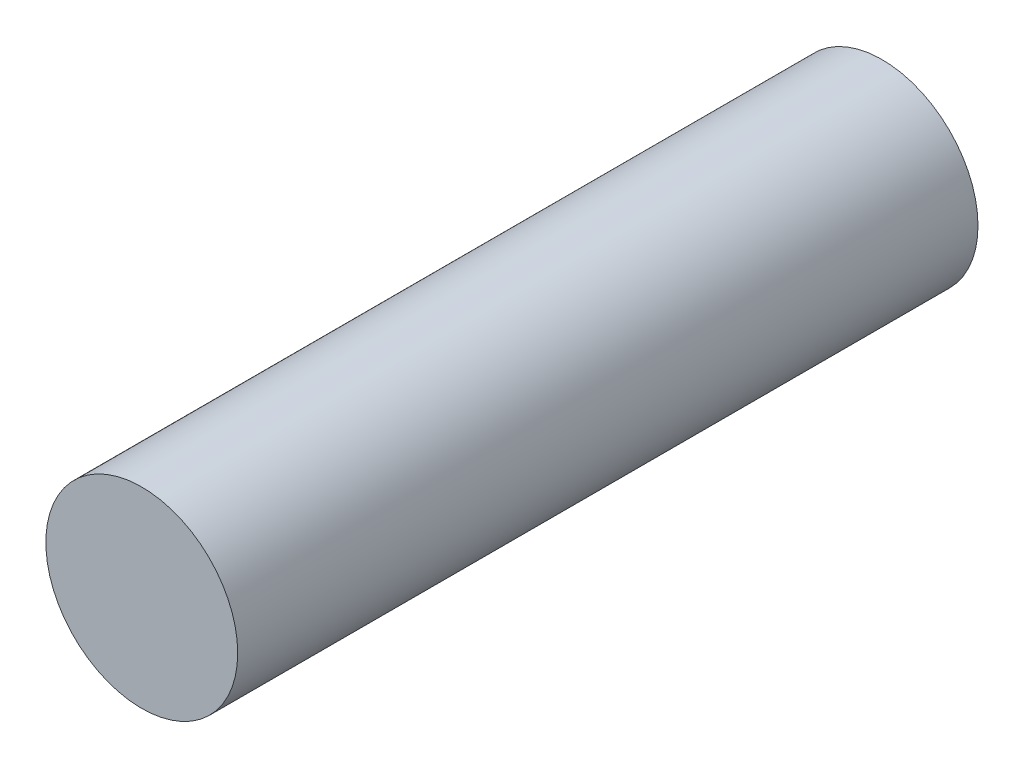
SolidWorks part; units mm, degrees
ref_plane "Front Plane" through (0, 0, 0) normal (0, 0, 1) x (1, 0, 0)
ref_plane "Top Plane" through (0, 0, 0) normal (0, 1, 0) x (1, 0, 0)
ref_plane "Right Plane" through (0, 0, 0) normal (1, 0, 0) x (0, 0, -1)
sketch "Sketch1" plane through (0, 0, 0) normal (0, 0, 1) x (1, 0, 0)
  circle A0 centre (0, 0) radius 3.175
  dimension "D1" = 6.35
extrude "Boss-Extrude1" add sketch "Sketch1" along normal blind 24.5
